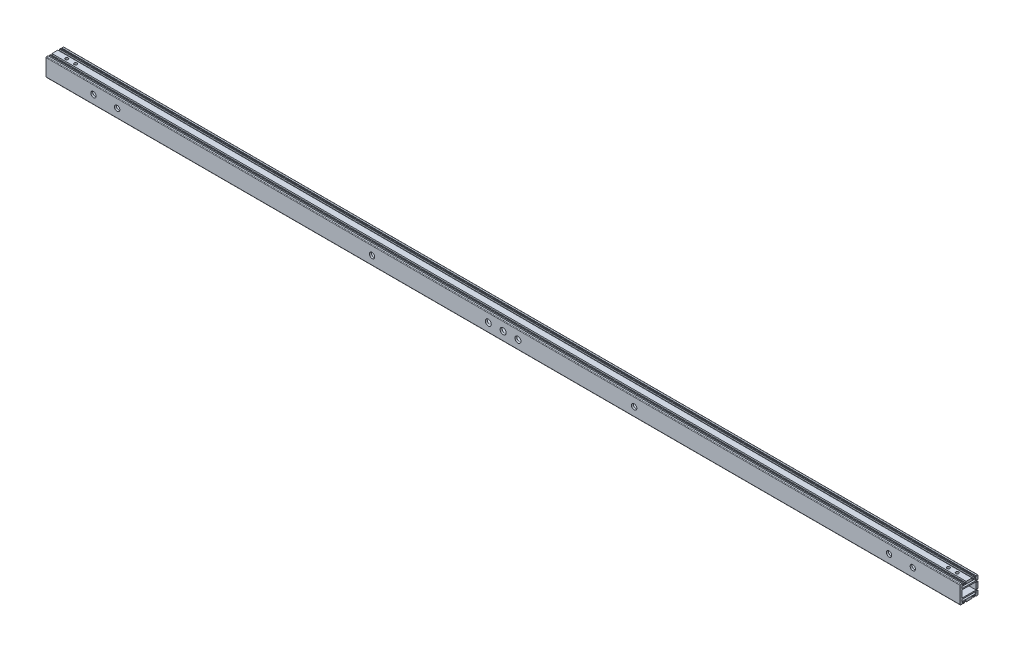
SolidWorks part; units mm, degrees
ref_plane "前视基准面" through (0, 0, 0) normal (0, 0, 1) x (1, 0, 0)
ref_plane "上视基准面" through (0, 0, 0) normal (0, 1, 0) x (1, 0, 0)
ref_plane "右视基准面" through (0, 0, 0) normal (1, 0, 0) x (0, 0, -1)
sketch "草图1" plane through (0, 0, 0) normal (1, 0, 0) x (0, 0, -1)
  line L0 (-15, 15) -> (15, -15) construction
  line L1 (-14, 15) -> (-11.5, 15)
  line L2 (-15, 14) -> (-15, -14)
  line L3 (-14, -15) -> (-11.5, -15)
  line L4 (15, 14) -> (15, 8)
  line L5 (15, 15) -> (-15, -15) construction
  line L6 (-11.5, 15) -> (-11.5, 13.5)
  line L7 (-11.5, 13.5) -> (-11.4, 13.5)
  line L8 (-11, 13.1) -> (-11, 12)
  line L9 (-11, 12) -> (-9.5, 12)
  line L10 (-9.5, 12) -> (-9.5, 15)
  line L11 (-9.5, 15) -> (-8, 15)
  line L12 (-8, 15) -> (-8, 12.5)
  line L13 (-8, 12.5) -> (-5, 12.5)
  line L14 (-5, 12.5) -> (-5, 15)
  line L15 (-5, 15) -> (5, 15)
  line L16 (0, 21.5201) -> (0, -18.309) construction
  line L17 (0, 55) -> (0, -55) construction
  line L18 (5, 12.5) -> (5, 15)
  line L19 (8, 12.5) -> (5, 12.5)
  line L20 (8, 15) -> (8, 12.5)
  line L21 (9.5, 15) -> (8, 15)
  line L22 (9.5, 12) -> (9.5, 15)
  line L23 (11, 12) -> (9.5, 12)
  line L24 (11, 13.1) -> (11, 12)
  line L25 (11.5, 13.5) -> (11.4, 13.5)
  line L26 (11.5, 15) -> (11.5, 13.5)
  line L27 (8, 15) -> (9.5, 15)
  line L28 (11.5, 15) -> (14, 15)
  line L29 (-19.8303, 0) -> (22.13, 0) construction
  line L30 (55, 0) -> (-55, 0) construction
  line L31 (8, -15) -> (9.5, -15)
  line L32 (11.5, -15) -> (11.5, -13.5)
  line L33 (11.5, -13.5) -> (11.4, -13.5)
  line L34 (11, -13.1) -> (11, -12)
  line L35 (11, -12) -> (9.5, -12)
  line L36 (9.5, -12) -> (9.5, -15)
  line L37 (9.5, -15) -> (8, -15)
  line L38 (8, -15) -> (8, -12.5)
  line L39 (8, -12.5) -> (5, -12.5)
  line L40 (5, -12.5) -> (5, -15)
  line L41 (-5, -15) -> (5, -15)
  line L42 (-5, -12.5) -> (-5, -15)
  line L43 (-8, -12.5) -> (-5, -12.5)
  line L44 (-8, -15) -> (-8, -12.5)
  line L45 (-9.5, -15) -> (-8, -15)
  line L46 (-9.5, -12) -> (-9.5, -15)
  line L47 (-11, -12) -> (-9.5, -12)
  line L48 (-11, -13.1) -> (-11, -12)
  line L49 (-11.5, -13.5) -> (-11.4, -13.5)
  line L50 (-11.5, -15) -> (-11.5, -13.5)
  line L51 (-9.5, -15) -> (-8, -15)
  line L52 (-5, -15) -> (5, -15)
  line L53 (8, -15) -> (9.5, -15)
  line L54 (11.5, -15) -> (14, -15)
  line L55 (15, 8) -> (12.5, 8)
  line L56 (12.5, 8) -> (12.5, 5)
  line L57 (12.5, 5) -> (15, 5)
  line L58 (12.5, -5) -> (15, -5)
  line L59 (12.5, -8) -> (12.5, -5)
  line L60 (15, -8) -> (12.5, -8)
  line L61 (15, 5) -> (15, -5)
  line L62 (15, -8) -> (15, -14)
  line L63 (12, -10.5) -> (12, -8.5)
  line L64 (-11.5, 11) -> (11.5, 11)
  line L65 (-12, 10.5) -> (-12, 8.5)
  line L66 (-11.5, 8) -> (11.5, 8)
  line L67 (12, 10.5) -> (12, 8.5)
  line L68 (-11.5, -8) -> (11.5, -8)
  line L69 (-12, -10.5) -> (-12, -8.5)
  line L70 (-11.5, -11) -> (11.5, -11)
  line L72 (-11.75, 6) -> (11.75, 6)
  line L73 (-11.75, 6) -> (-11.75, -6)
  line L74 (-11.75, -6) -> (11.75, -6)
  line L75 (11.75, 6) -> (11.75, -6)
  arc A0 (12, 8.5) -> (11.5, 8) centre (11.5, 8.5) cw
  arc A1 (11.5, 11) -> (12, 10.5) centre (11.5, 10.5) cw
  arc A2 (-11.5, 11) -> (-12, 10.5) centre (-11.5, 10.5) ccw
  arc A3 (-11.5, 8) -> (-12, 8.5) centre (-11.5, 8.5) cw
  arc A4 (-11, -13.1) -> (-11.4, -13.5) centre (-11.4, -13.1) cw
  arc A5 (11.4, -13.5) -> (11, -13.1) centre (11.4, -13.1) cw
  arc A6 (11.4, 13.5) -> (11, 13.1) centre (11.4, 13.1) ccw
  arc A7 (-11, 13.1) -> (-11.4, 13.5) centre (-11.4, 13.1) ccw
  arc A8 (-11.5, -8) -> (-12, -8.5) centre (-11.5, -8.5) ccw
  arc A9 (-11.5, -11) -> (-12, -10.5) centre (-11.5, -10.5) cw
  arc A10 (11.5, -11) -> (12, -10.5) centre (11.5, -10.5) ccw
  arc A11 (12, -8.5) -> (11.5, -8) centre (11.5, -8.5) ccw
  arc A12 (14, 15) -> (15, 14) centre (14, 14) cw
  arc A13 (14, -15) -> (15, -14) centre (14, -14) ccw
  arc A14 (-15, -14) -> (-14, -15) centre (-14, -14) ccw
  arc A15 (-15, 14) -> (-14, 15) centre (-14, 14) cw
  point P69 (12, 11)
  point P72 (-12, 11)
  point P77 (-11, -13.5)
  point P80 (11, -13.5)
  point P83 (11, 13.5)
  point P86 (-11, 13.5)
  point P99 (-12, -11)
  point P100 (12, -11)
  dimension "D17" = 0.5
  dimension "D18" = 0.4
  dimension "D21" = 1
  dimension "D1" = 3.5
  dimension "D2" = 1.5
  dimension "D3" = 0.5
  dimension "D4" = 1.5
  dimension "D5" = 3
  dimension "D6" = 30
  dimension "D7" = 30
  dimension "D8" = 1.5
  dimension "D9" = 2.5
  dimension "D10" = 3
  dimension "D11" = 2.5
  dimension "D12" = 7
  dimension "D13" = 3
  dimension "D14" = 4
  dimension "D15" = 3
  dimension "D16" = 24
  dimension "D19" = 23.5
  dimension "D20" = 12
extrude "凸台-拉伸1" add sketch "草图1" along normal mid plane 1542 contours A15 L2 A14 L3 L50 L49 A4 L48 L47 L46 L45 L44 L43 L42 L41 L40 L39 L38 L31 L36 L35 L34 A5 L33 L32 L54 A13 L62 L60 L59 L58 L61 L57 L56 L55 L4 A12 L28 L26 L25 A6 L24 L23 L22 L21 L20 L19 L18 L15 L14 L13
sketch "草图10" plane through (0, 0, -15) normal (0, 0, -1) x (-1, 0, 0)
  line L0 (-771, -15) -> (771, -15) construction
  circle A0 centre (-651, 0) radius 4.5
  circle A1 centre (-221, 0) radius 4.5
  circle A2 centre (221, 0) radius 4.5
  circle A3 centre (651, 0) radius 4.5
  circle A4 centre (691, 0) radius 4.5
  circle A5 centre (-691, 0) radius 4.5
  dimension "D1" = 9
  dimension "D2" = 40
  dimension "D3" = 15
  dimension "D4" = 40
  dimension "D5" = 15
hole_wizard "M6 螺纹孔3" positions "草图12" profile "草图11" tap size "M6" standard "GB"
sketch "草图12" plane through (0, 0, -15) normal (0, 0, -1) x (-1, 0, 0)
  line L0 (-771, -8) -> (-771, -14) construction
  line L1 (-771, -15) -> (771, -15) construction
  line L2 (771, -8) -> (771, -14) construction
  point P0 (-751, 0)
  point P1 (-736, 0)
  point P3 (736, 0)
  point P5 (751, 0)
  dimension "D1" = 20
  dimension "D2" = 15
  dimension "D3" = 15
  dimension "D4" = 15
  dimension "D5" = 20
  dimension "D6" = 15
  dimension "D7" = 15
  dimension "D8" = 15
sketch "草图11" plane through (751, 0, -15) normal (1, 0, 0) x (0, 1, 0)
  line L0 (0, 0) -> (0, 16.5022)
  line L1 (0, 16.5022) -> (2.5, 15)
  line L2 (2.5, 15) -> (2.5, 0)
  line L5 (2.5, 0) -> (0, 0)
  line L10 (0, 16.5022) -> (-2.5, 15) construction
  line L11 (0, -6.35) -> (0, 107.95) construction
  dimension "螺纹孔钻头直径" = 5
  dimension "螺纹孔钻头深度" = 15
  dimension "导头角度" = 118
cosmetic thread "孔螺蚊线9" parameters "D1"=3.25, "D2"=6
cosmetic thread "孔螺蚊线10" parameters "D1"=3.25, "D2"=6
cosmetic thread "孔螺蚊线11" parameters "D1"=3.25, "D2"=6
cosmetic thread "孔螺蚊线12" parameters "D1"=3.25, "D2"=6
sketch "草图13" plane through (0, 0, -15) normal (0, 0, -1) x (-1, 0, 0)
  circle A0 centre (0, 0) radius 5.05
  circle A1 centre (25, 0) radius 5.05
  circle A2 centre (-25, 0) radius 5.05
  dimension "D1" = 10.1
  dimension "D2" = 25
  dimension "D3" = 25
extrude "切除-拉伸6" cut sketch "草图13" against normal through all
hole_wizard "M6 螺纹孔4" positions "草图15" profile "草图14" tap size "M6" standard "GB"
sketch "草图15" plane through (0, 0, -15) normal (0, 0, -1) x (-1, 0, 0)
  line L0 (771, -8) -> (771, -14) construction
  line L1 (-771, -15) -> (771, -15) construction
  line L2 (-771, -8) -> (-771, -14) construction
  point P0 (-411, 0)
  point P2 (-351, 0)
  point P4 (351, 0)
  point P6 (411, 0)
  dimension "D1" = 60
  dimension "D2" = 360
  dimension "D3" = 15
  dimension "D4" = 60
  dimension "D5" = 360
sketch "草图14" plane through (411, 0, -15) normal (1, 0, 0) x (0, 1, 0)
  line L0 (0, 0) -> (0, 16.5022)
  line L1 (0, 16.5022) -> (2.5, 15)
  line L2 (2.5, 15) -> (2.5, 0)
  line L5 (2.5, 0) -> (0, 0)
  line L10 (0, 16.5022) -> (-2.5, 15) construction
  line L11 (0, -6.35) -> (0, 107.95) construction
  dimension "螺纹孔钻头直径" = 5
  dimension "螺纹孔钻头深度" = 15
  dimension "导头角度" = 118
cosmetic thread "孔螺蚊线13" parameters "D1"=3.25, "D2"=6
cosmetic thread "孔螺蚊线14" parameters "D1"=3.25, "D2"=6
cosmetic thread "孔螺蚊线15" parameters "D1"=3.25, "D2"=6
cosmetic thread "孔螺蚊线16" parameters "D1"=3.25, "D2"=6
extrude "切除-拉伸7" cut sketch "草图10" against normal through all
hole_wizard "M6 螺纹孔5" positions "草图17" profile "草图16" tap size "M6" standard "GB"
sketch "草图17" plane through (0, 15, 0) normal (0, 1, 0) x (-1, 0, 0)
  line L0 (-771, 15) -> (771, 15) construction
  line L1 (771, 14) -> (771, 11.5) construction
  line L2 (-771, 5) -> (-771, -5) construction
  point P1 (-751, 0)
  point P3 (-736, 0)
  point P5 (736, 0)
  point P7 (751, 0)
  dimension "D1" = 15
  dimension "D2" = 20
  dimension "D3" = 15
  dimension "D4" = 15
  dimension "D5" = 20
  dimension "D6" = 15
  dimension "D7" = 15
  dimension "D8" = 15
sketch "草图16" plane through (751, 15, 0) normal (1, 0, 0) x (0, 0, 1)
  line L0 (0, 0) -> (0, 16.5022)
  line L1 (0, 16.5022) -> (2.5, 15)
  line L2 (2.5, 15) -> (2.5, 0)
  line L5 (2.5, 0) -> (0, 0)
  line L10 (0, 16.5022) -> (-2.5, 15) construction
  line L11 (0, -6.35) -> (0, 107.95) construction
  dimension "螺纹孔钻头直径" = 5
  dimension "螺纹孔钻头深度" = 15
  dimension "导头角度" = 118
cosmetic thread "孔螺蚊线17" parameters "D1"=9, "D2"=6
cosmetic thread "孔螺蚊线18" parameters "D1"=9, "D2"=6
cosmetic thread "孔螺蚊线19" parameters "D1"=9, "D2"=6
cosmetic thread "孔螺蚊线20" parameters "D1"=9, "D2"=6
